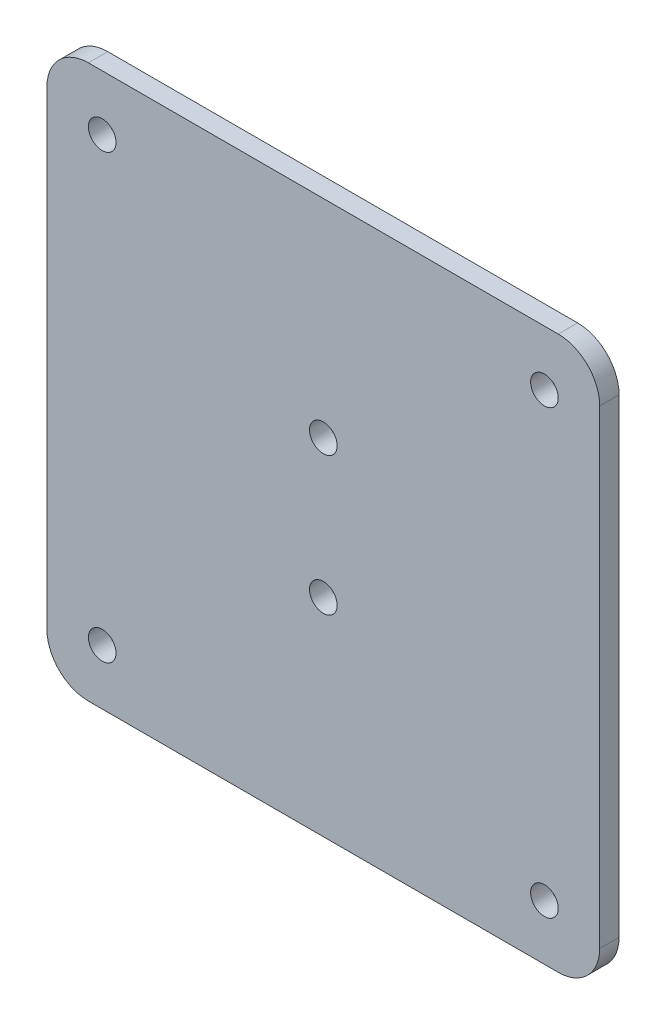
SolidWorks part; units mm, degrees
ref_plane "Plan de face" through (0, 0, 0) normal (0, 0, 1) x (1, 0, 0)
ref_plane "Plan de dessus" through (0, 0, 0) normal (0, 1, 0) x (1, 0, 0)
ref_plane "Plan de droite" through (0, 0, 0) normal (1, 0, 0) x (0, 0, -1)
sketch "Esquisse3" plane through (0, 0, 0) normal (0, 0, 1) x (1, 0, 0)
  line L1 (-100, -100) -> (100, -100)
  line L2 (-100, -100) -> (-100, 100)
  line L3 (-100, 100) -> (100, 100)
  line L4 (100, -100) -> (100, 100)
  line L5 (-80, -80) -> (80, -80) construction
  line L6 (-80, -80) -> (-80, 80) construction
  line L7 (-80, 80) -> (80, 80) construction
  line L8 (80, -80) -> (80, 80) construction
  circle A0 centre (80, 80) radius 5
  circle A1 centre (80, -80) radius 5
  circle A2 centre (-80, -80) radius 5
  circle A3 centre (-80, 80) radius 5
  point P4 (0, 0)
  dimension "D9" = 10
  dimension "D10" = 10
  dimension "D11" = 10
  dimension "D12" = 10
  dimension "D1" = 200
  dimension "D2" = 200
  dimension "D3" = 100
  dimension "D4" = 100
  dimension "D5" = 20
  dimension "D6" = 20
  dimension "D7" = 20
  dimension "D8" = 20
extrude "Boss.-Extru.2" add sketch "Esquisse3" along normal blind 7
fillet "Congé1" radius 15 4 edges at (-100, -100, 3.5) (-100, 100, 3.5) (100, 100, 3.5) (100, -100, 3.5)
sketch "Esquisse4" plane through (0, 0, 0) normal (0, 0, -1) x (-1, 0, 0)
  line L0 (0, -25) -> (0, 25) construction
  circle A0 centre (0, -25) radius 5
  circle A1 centre (0, 25) radius 5
  dimension "D3" = 10
  dimension "D4" = 10
  dimension "D1" = 25
  dimension "D2" = 50
extrude "Enlèv. mat.-Extru.1" cut sketch "Esquisse4" against normal blind 10
